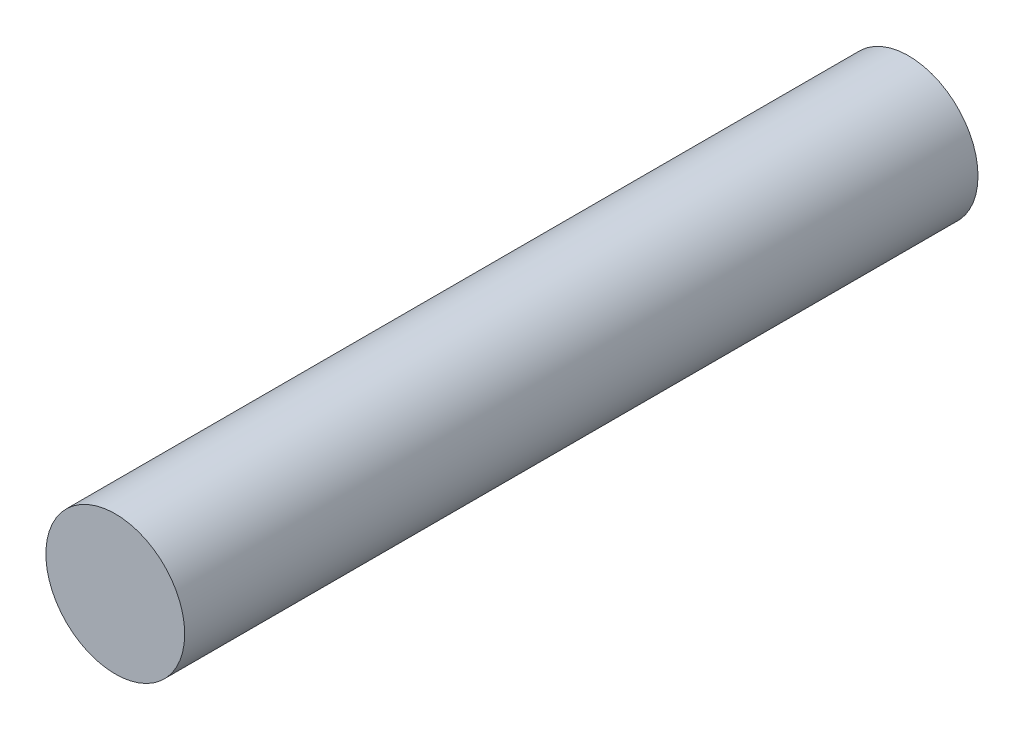
SolidWorks part; units mm, degrees
ref_plane "Front Plane" through (0, 0, 0) normal (0, 0, 1) x (1, 0, 0)
ref_plane "Top Plane" through (0, 0, 0) normal (0, 1, 0) x (1, 0, 0)
ref_plane "Right Plane" through (0, 0, 0) normal (1, 0, 0) x (0, 0, -1)
other "Configuration Table"
sketch "Sketch1" plane through (0, 0, 0) normal (0, 0, 1) x (1, 0, 0)
  circle A0 centre (0, 0) radius 35
extrude "Boss-Extrude1" add sketch "Sketch1" along normal blind 400
